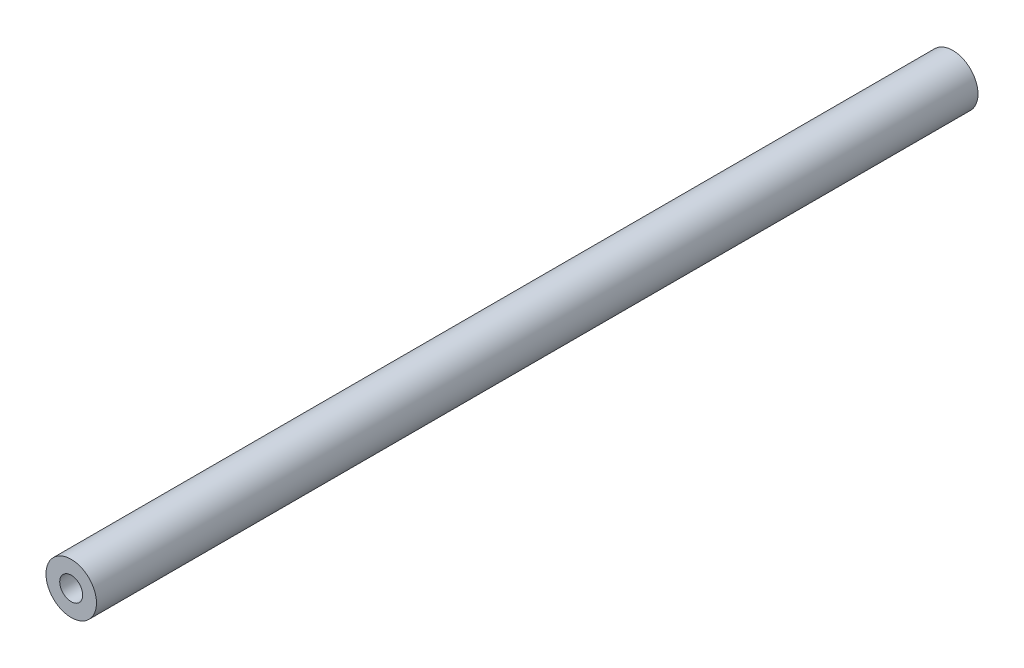
SolidWorks part; units mm, degrees
material "ABS"
ref_plane "Front Plane" through (0, 0, 0) normal (0, 0, 1) x (1, 0, 0)
ref_plane "Top Plane" through (0, 0, 0) normal (0, 1, 0) x (1, 0, 0)
ref_plane "Right Plane" through (0, 0, 0) normal (1, 0, 0) x (0, 0, -1)
sketch "Sketch1" plane through (0, 0, 0) normal (0, 0, 1) x (1, 0, 0)
  circle A0 centre (0, 0) radius 1.25
  circle A1 centre (0, 0) radius 2.75
  dimension "D1" = 2.5
  dimension "D2" = 5.5
extrude "Boss-Extrude1" add sketch "Sketch1" along normal blind 96
